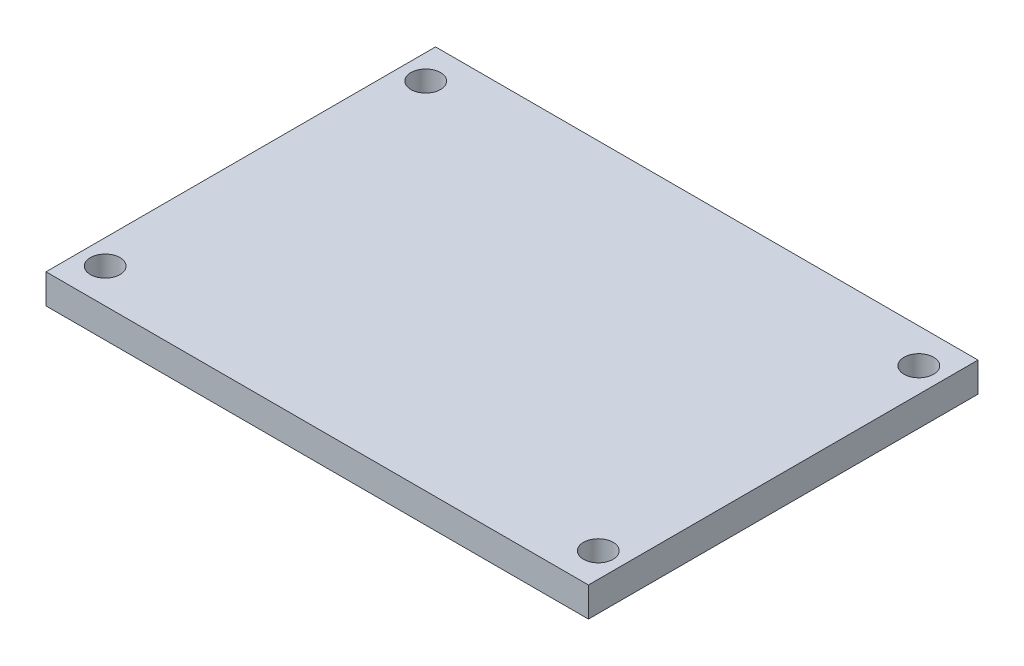
SolidWorks part; units mm, degrees
ref_plane "Front Plane" through (0, 0, 0) normal (0, 0, 1) x (1, 0, 0)
ref_plane "Top Plane" through (0, 0, 0) normal (0, 1, 0) x (1, 0, 0)
ref_plane "Right Plane" through (0, 0, 0) normal (1, 0, 0) x (0, 0, -1)
sketch "Sketch2" plane through (0, 0, 0) normal (0, 1, 0) x (1, 0, 0)
  line L1 (-34.925, -25.0825) -> (34.925, -25.0825)
  line L2 (-34.925, -25.0825) -> (-34.925, 25.0825)
  line L3 (-34.925, 25.0825) -> (34.925, 25.0825)
  line L4 (34.925, -25.0825) -> (34.925, 25.0825)
  line L5 (-34.925, -25.0825) -> (34.925, 25.0825) construction
  line L6 (-34.925, 25.0825) -> (34.925, -25.0825) construction
  point P0 (0, 0)
  dimension "D1" = 50.165
  dimension "D2" = 69.85
extrude "Boss-Extrude1" add sketch "Sketch2" along normal blind 3.81
sketch "Sketch3" plane through (0, 3.81, 0) normal (0, 1, 0) x (1, 0, 0)
  line L1 (-31.75, -20.6375) -> (31.75, -20.6375) construction
  line L2 (-31.75, -20.6375) -> (-31.75, 20.6375) construction
  line L3 (-31.75, 20.6375) -> (31.75, 20.6375) construction
  line L4 (31.75, -20.6375) -> (31.75, 20.6375) construction
  line L5 (-31.75, -20.6375) -> (31.75, 20.6375) construction
  line L6 (-31.75, 20.6375) -> (31.75, -20.6375) construction
  circle A0 centre (-31.75, 20.6375) radius 1.905
  circle A1 centre (31.75, 20.6375) radius 1.905
  circle A2 centre (31.75, -20.6375) radius 1.905
  circle A3 centre (-31.75, -20.6375) radius 1.905
  point P0 (0, 0)
  dimension "D3" = 3.81
  dimension "D1" = 41.275
  dimension "D2" = 63.5
extrude "Cut-Extrude1" cut sketch "Sketch3" against normal through all both and the other way through all
